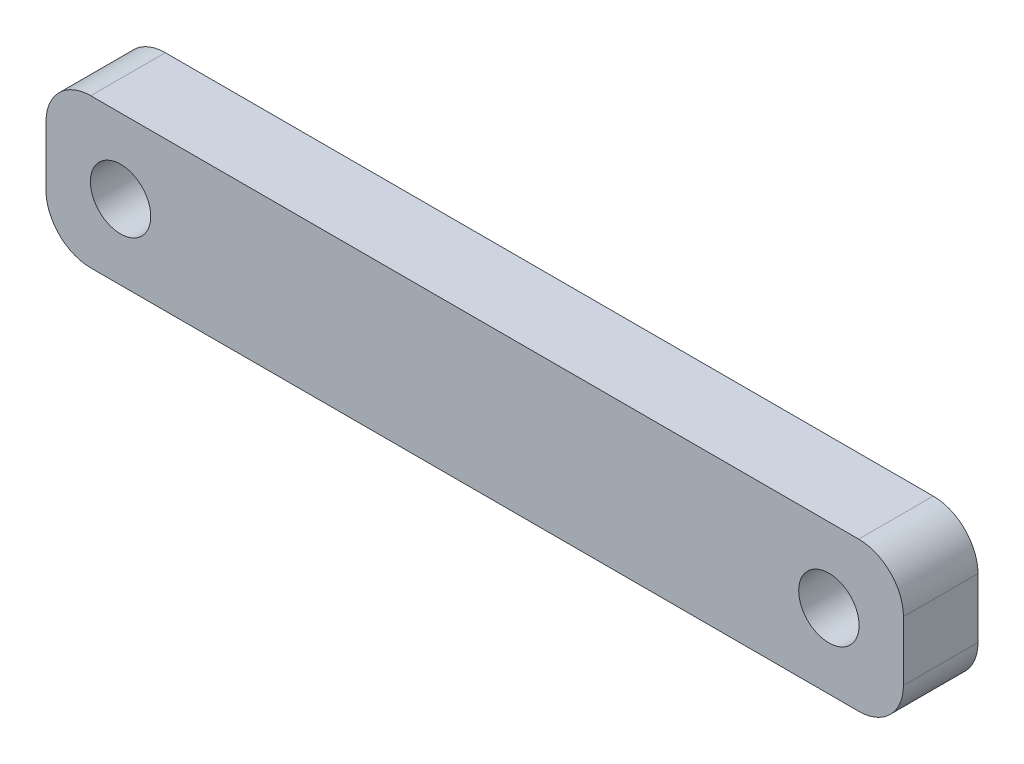
SolidWorks part; units mm, degrees
ref_plane "前视基准面" through (0, 0, 0) normal (0, 0, 1) x (1, 0, 0)
ref_plane "上视基准面" through (0, 0, 0) normal (0, 1, 0) x (1, 0, 0)
ref_plane "右视基准面" through (0, 0, 0) normal (1, 0, 0) x (0, 0, -1)
sketch "草图5" plane through (0, 0, 0) normal (0, 1, 0) x (1, 0, 0)
  line L1 (0, 0) -> (57.5, 0)
  line L2 (0, 0) -> (0, 5)
  line L3 (0, 5) -> (57.5, 5)
  line L4 (57.5, 0) -> (57.5, 5)
  dimension "D1" = 57.5
  dimension "D2" = 5
extrude "凸台-拉伸3" add sketch "草图5" along normal blind 10
sketch "草图6" plane through (0, 0, -5) normal (0, 0, -1) x (-1, 0, 0)
  line L0 (-57.5, 5) -> (-52.5, 5) construction
  line L1 (-57.5, 10) -> (-57.5, 0) construction
  line L2 (-52.5, 5) -> (-5, 5) construction
  line L3 (-5, 5) -> (0, 5) construction
  line L4 (0, 10) -> (0, 0) construction
  circle A0 centre (-52.5, 5) radius 2.025
  circle A1 centre (-5, 5) radius 2.025
  dimension "D3" = 4.05
  dimension "D1" = 5
  dimension "D2" = 47.5
extrude "切除-拉伸4" cut sketch "草图6" against normal through all
fillet "圆角4" radius 3 4 edges at (0, 0, -2.5) (0, 10, -2.5) (57.5, 10, -2.5) (57.5, 0, -2.5)
